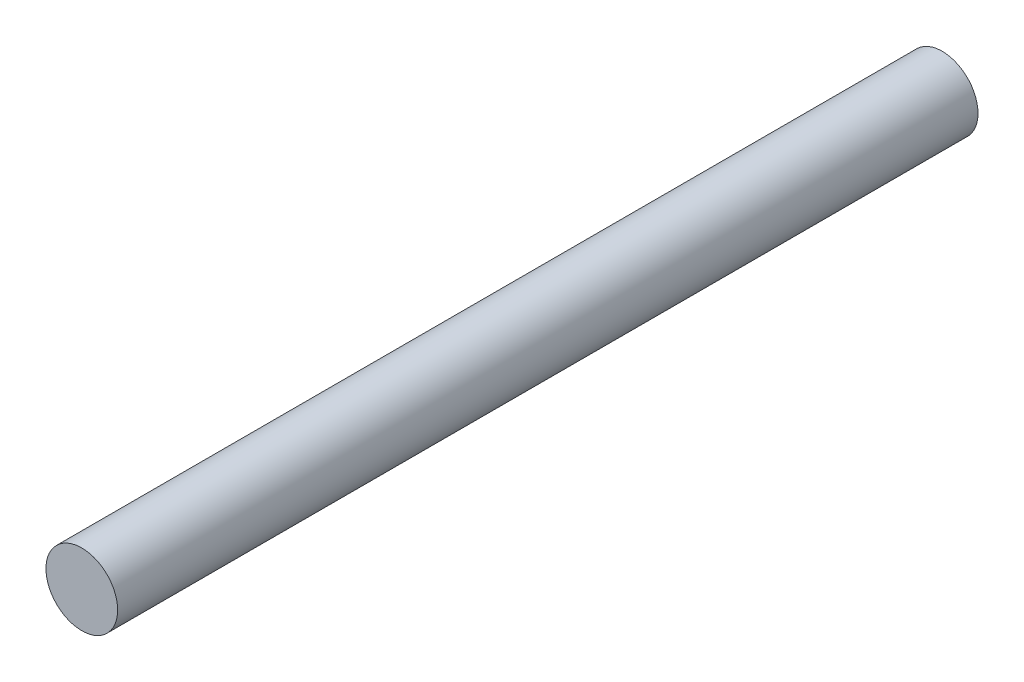
SolidWorks part; units mm, degrees
material "Nickel"
ref_plane "Front Plane" through (0, 0, 0) normal (0, 0, 1) x (1, 0, 0)
ref_plane "Top Plane" through (0, 0, 0) normal (0, 1, 0) x (1, 0, 0)
ref_plane "Right Plane" through (0, 0, 0) normal (1, 0, 0) x (0, 0, -1)
sketch "Sketch1" plane through (0, 0, 0) normal (0, 0, 1) x (1, 0, 0)
  circle A0 centre (0, 0) radius 1.25
  dimension "D1" = 2.5
extrude "Boss-Extrude1" add sketch "Sketch1" along normal blind 30
